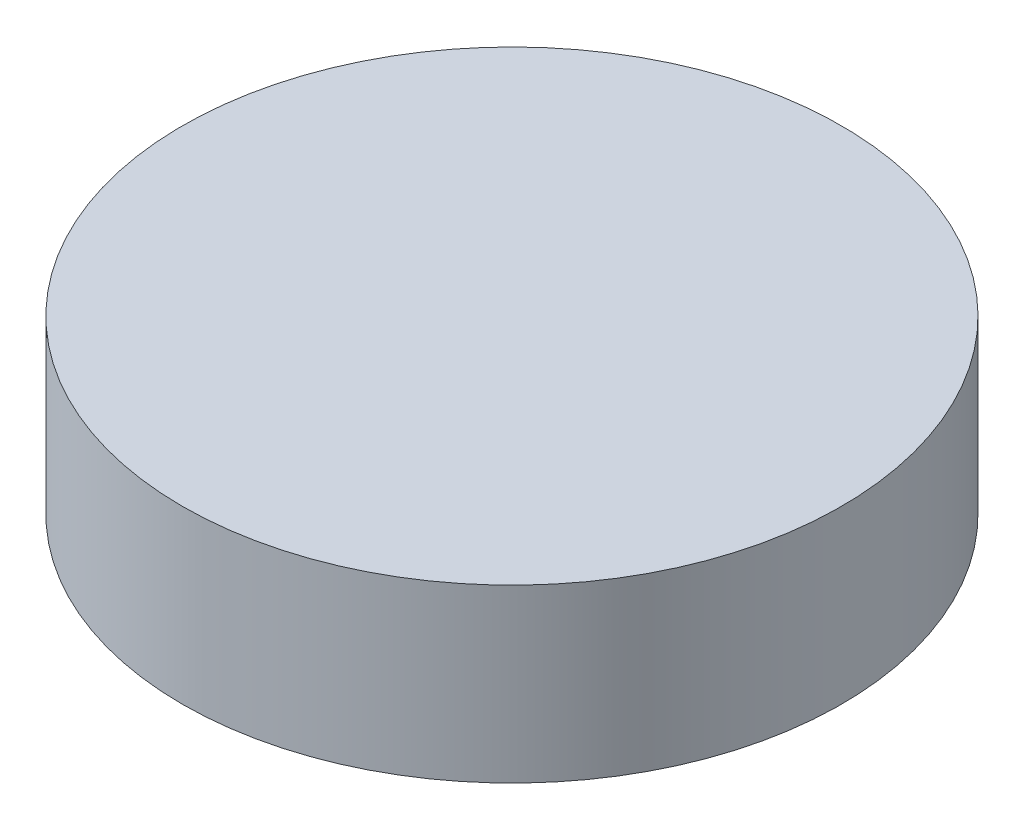
SolidWorks part; units mm, degrees
ref_plane "Front Plane" through (0, 0, 0) normal (0, 0, 1) x (1, 0, 0)
ref_plane "Top Plane" through (0, 0, 0) normal (0, 1, 0) x (1, 0, 0)
ref_plane "Right Plane" through (0, 0, 0) normal (1, 0, 0) x (0, 0, -1)
sketch "Sketch1" plane through (0, 0, 0) normal (0, 1, 0) x (1, 0, 0)
  circle A0 centre (0, -2.0762) radius 48.8333
  point P2 (0, -2.0762)
extrude "Boss-Extrude1" add sketch "Sketch1" along normal blind 25.4
